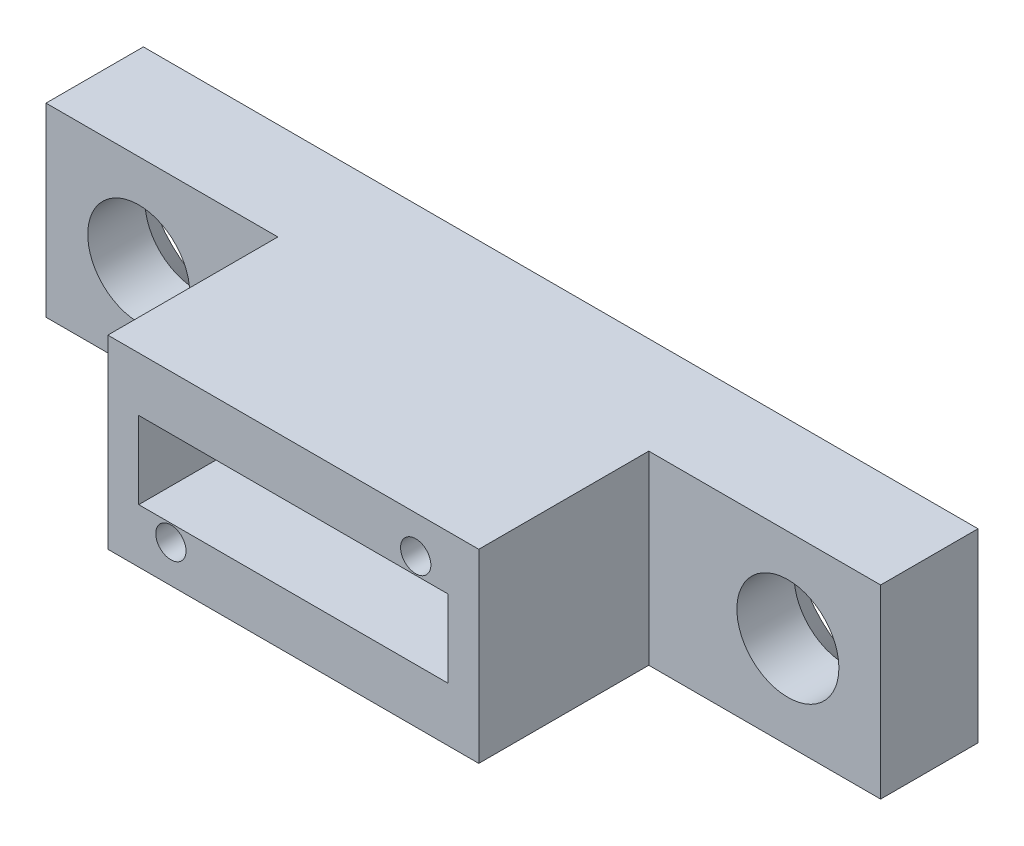
SolidWorks part; units mm, degrees
ref_plane "Plan de face" through (0, 0, 0) normal (0, 0, 1) x (1, 0, 0)
ref_plane "Plan de dessus" through (0, 0, 0) normal (0, 1, 0) x (1, 0, 0)
ref_plane "Plan de droite" through (0, 0, 0) normal (1, 0, 0) x (0, 0, -1)
sketch "Esquisse1" plane through (0, 0, 0) normal (0, 0, 1) x (1, 0, 0)
  line L1 (0, 0) -> (-27, 0)
  line L2 (0, 0) -> (0, 6)
  line L3 (0, 6) -> (-27, 6)
  line L4 (-27, 0) -> (-27, 6)
  line L11 (-27, 3) -> (-24, 3) construction
  line L12 (-24, 3) -> (-3, 3) construction
  line L13 (-3, 3) -> (0, 3) construction
  circle A0 centre (-24, 3) radius 1.65
  circle A1 centre (-3, 3) radius 1.65
  dimension "D4" = 3.3
  dimension "D2" = 3
  dimension "D3" = 21
  dimension "D5" = 6
extrude "Boss.-Extru.1" add sketch "Esquisse1" along normal blind 3.15
sketch "Esquisse3" plane through (0, 0, 3.15) normal (0, 0, 1) x (1, 0, 0)
  line L0 (-27, 0) -> (0, 0) construction
  line L1 (0, 6) -> (-27, 6) construction
  line L4 (-19.5, 0) -> (-7.5, 0)
  line L5 (-19.5, 0) -> (-19.5, 6)
  line L6 (-19.5, 6) -> (-7.5, 6)
  line L7 (-7.5, 0) -> (-7.5, 6)
  line L8 (-19.5, 0) -> (-7.5, 6) construction
  line L9 (-19.5, 6) -> (-7.5, 0) construction
  line L11 (0, 6) -> (-27, 0) construction
  point P6 (-13.5, 3)
  point P7 (-13.5, 3)
  dimension "D2" = 12
extrude "Boss.-Extru.2" add sketch "Esquisse3" along normal blind 5.5
sketch "Esquisse4" plane through (0, 0, 8.65) normal (0, 0, 1) x (1, 0, 0)
  line L0 (-19.5, 0) -> (-7.5, 6) construction
  line L4 (-8.5, 1.75) -> (-18.5, 1.75)
  line L5 (-8.5, 1.75) -> (-8.5, 4.25)
  line L6 (-8.5, 4.25) -> (-18.5, 4.25)
  line L7 (-18.5, 1.75) -> (-18.5, 4.25)
  line L8 (-8.5, 1.75) -> (-18.5, 4.25) construction
  line L9 (-8.5, 4.25) -> (-18.5, 1.75) construction
  point P2 (-13.5, 3)
  point P6 (-13.5, 3)
  dimension "D1" = 10
  dimension "D2" = 2.5
extrude "Enlèv. mat.-Extru.1" cut sketch "Esquisse4" against normal blind 10
sketch "Esquisse5" plane through (0, 0, 8.65) normal (0, 0, 1) x (1, 0, 0)
  line L0 (-18.5, 4.25) -> (-8.5, 1.75) construction
  line L1 (-8.5, 1.75) -> (-13.5, 3) construction
  line L2 (-13.5, 3) -> (-13.5, 4.785) construction
  line L3 (-13.5, 4.785) -> (-9.54, 4.785) construction
  line L4 (-9.54, 4.785) -> (-13.5, 3) construction
  line L5 (-13.5, 3) -> (-13.5, 1.215) construction
  line L6 (-13.5, 1.215) -> (-17.46, 1.215) construction
  circle A0 centre (-9.54, 4.785) radius 0.49
  circle A1 centre (-17.46, 1.215) radius 0.49
  dimension "D1" = 3.57
  dimension "D3" = 0.98
  dimension "D2" = 7.92
extrude "Enlèv. mat.-Extru.2" cut sketch "Esquisse5" against normal blind 1.5
chamfer "Chanfrein1" distance 1.3 angle 45 2 edges at (-22.35, 3, 0) (-1.35, 3, 0)
